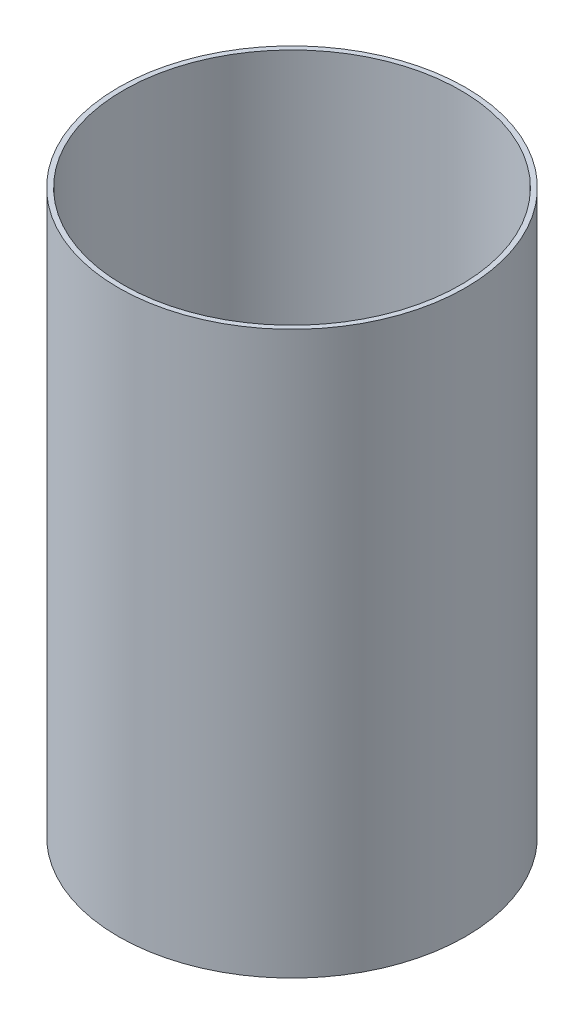
SolidWorks part; units mm, degrees
ref_plane "Front Plane" through (0, 0, 0) normal (0, 0, 1) x (1, 0, 0)
ref_plane "Top Plane" through (0, 0, 0) normal (0, 1, 0) x (1, 0, 0)
ref_plane "Right Plane" through (0, 0, 0) normal (1, 0, 0) x (0, 0, -1)
sketch "Sketch1" plane through (0, 0, 0) normal (0, 1, 0) x (1, 0, 0)
  circle A0 centre (0, 0) radius 1.75
  dimension "D1" = 3.5
extrude "Boss-Extrude1" add sketch "Sketch1" along normal blind 3 and the other way blind 2.6653 contours A0
sketch "Sketch2" plane through (0, 3, 0) normal (0, 1, 0) x (1, 0, 0)
  circle A0 centre (0, 0) radius 1.7
  dimension "D1" = 3.4
extrude "Cut-Extrude1" cut sketch "Sketch2" along normal through all and the other way blind 3
